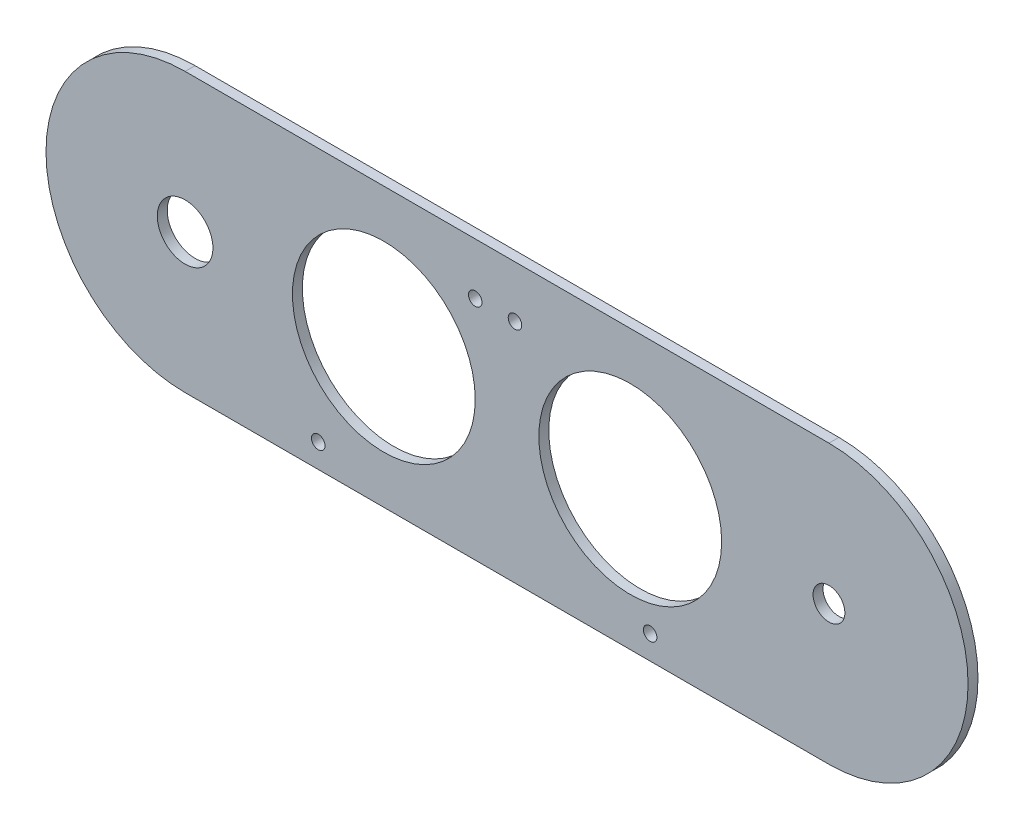
SolidWorks part; units mm, degrees
ref_plane "Plan1" through (0, 0, 0) normal (0, 0, 1) x (1, 0, 0)
ref_plane "Plan2" through (0, 0, 0) normal (0, 1, 0) x (1, 0, 0)
ref_plane "Plan3" through (0, 0, 0) normal (1, 0, 0) x (0, 0, -1)
sketch "Esquisse2" plane through (0, 0, 0) normal (0, 0, 1) x (1, 0, 0)
  line L0 (-60.5878, 50.043) -> (101.4122, 50.043)
  line L1 (-60.5878, -19.957) -> (101.4122, -19.957)
  line L2 (-60.5878, 15.043) -> (101.4122, 15.043) construction
  arc A0 (-60.5878, 50.043) -> (-60.5878, -19.957) centre (-60.5878, 15.043) ccw
  arc A1 (101.4122, 50.043) -> (101.4122, -19.957) centre (101.4122, 15.043) cw
  circle A2 centre (-60.5878, 15.043) radius 7
  circle A3 centre (101.4122, 15.043) radius 4
  circle A4 centre (51.4122, 15.043) radius 23
  circle A5 centre (-10.5878, 15.043) radius 23
  dimension "D2" = 35
  dimension "D5" = 46
  dimension "D6" = 46
  dimension "D7" = 8
  dimension "D8" = 14
  dimension "D1" = 162
  dimension "D3" = 50
  dimension "D4" = 62
extrude "Base-Extrusion" add sketch "Esquisse2" along normal blind 2.5
sketch "Esquisse9" plane through (0, 0, 2.5) normal (0, 0, 1) x (1, 0, 0)
  line L0 (-7.1251, 15.043) -> (51.4122, 15.043) construction
  circle A0 centre (12.4122, 37.043) radius 1.7
  dimension "D3" = 3.4
  dimension "D1" = 22
  dimension "D2" = 73
extrude "Enlèv. mat.-Extru.2" cut sketch "Esquisse9" against normal through all
pattern_linear "Répétition linéaire1" count 2 spacing 10
sketch "Esquisse10" plane through (0, 0, 2.5) normal (0, 0, 1) x (1, 0, 0)
  line L0 (48.4219, 15.043) -> (-10.5878, 15.043) construction
  circle A0 centre (-27.0878, -13.957) radius 1.7
  dimension "D3" = 3.4
  dimension "D1" = 29
  dimension "D2" = 33.5
extrude "Enlèv. mat.-Extru.3" cut sketch "Esquisse10" against normal through all
pattern_linear "Répétition linéaire2" count 2 spacing 83.5
